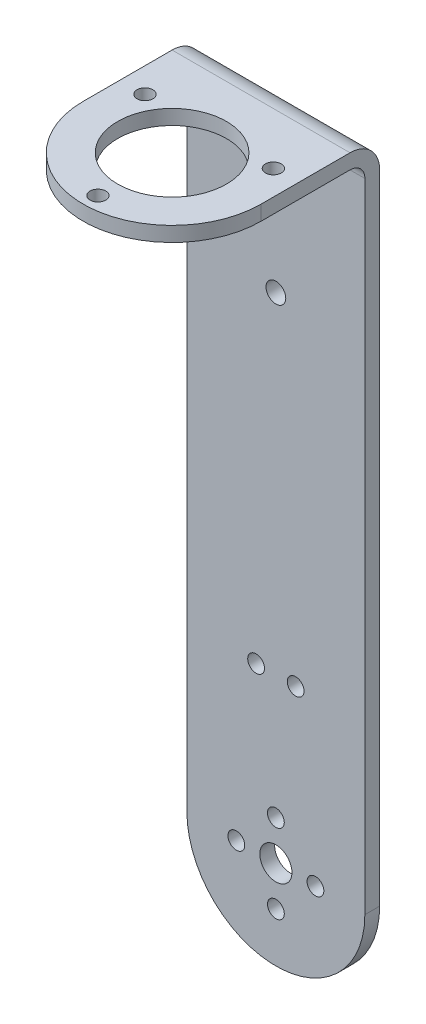
SolidWorks part; units mm, degrees
ref_plane "前视基准面" through (0, 0, 0) normal (0, 0, 1) x (1, 0, 0)
ref_plane "上视基准面" through (0, 0, 0) normal (0, 1, 0) x (1, 0, 0)
ref_plane "右视基准面" through (0, 0, 0) normal (1, 0, 0) x (0, 0, -1)
other "Configuration Table"
sketch "草图1" plane through (0, 0, 0) normal (0, 0, 1) x (1, 0, 0)
  line L0 (-18, 0) -> (-18, 135)
  line L1 (-18, 135) -> (18, 135)
  line L2 (18, 135) -> (18, 0)
  arc A0 (18, 0) -> (-18, 0) centre (0, 0) cw
  circle A1 centre (0, 0) radius 3.25
  circle A2 centre (-8, 0) radius 1.7
  circle A3 centre (8, 0) radius 1.7
  circle A4 centre (0, -8) radius 1.7
  circle A5 centre (0, 8) radius 1.7
  circle A6 centre (-4, 33) radius 1.7
  circle A7 centre (4, 33) radius 1.7
  circle A8 centre (0, 100) radius 2
extrude "01_Main_plate_135_W36_T3_EST_holes" add sketch "草图1" along normal blind 3
sketch "草图2" plane through (0, 135, 0) normal (0, 1, 0) x (1, 0, 0)
  line L0 (-18, 0) -> (18, 0)
  line L1 (18, 0) -> (18, -24)
  line L2 (-18, -24) -> (-18, 0)
  arc A0 (18, -24) -> (-18, -24) centre (0, -24) cw
  circle A1 centre (0, -24) radius 11
  circle A2 centre (0, -39) radius 1.6
  circle A3 centre (-12.9904, -16.5) radius 1.6
  circle A4 centre (12.9904, -16.5) radius 1.6
extrude "02_Flange_H42_hole22_EST" add sketch "草图2" against normal blind 3
fillet "03_Bend_inner_R3_EST" radius 3 1 edges at (0, 132, 3)
fillet "04_Bend_outer_R6_EST" radius 6 1 edges at (0, 135, 0)
